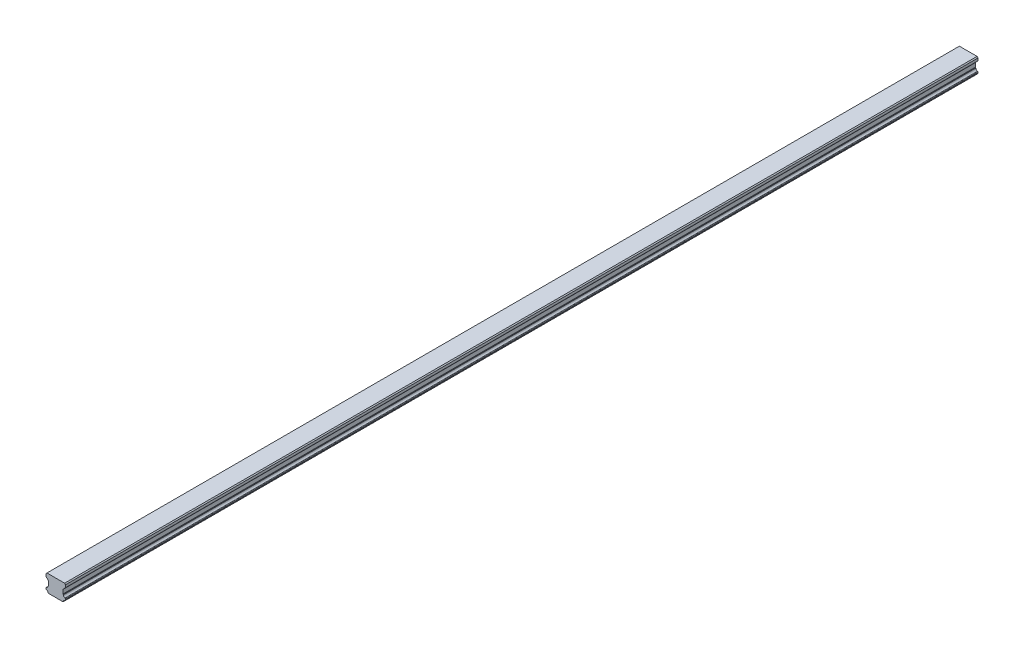
SolidWorks part; units mm, degrees
ref_plane "Спереди" through (0, 0, 0) normal (0, 0, 1) x (1, 0, 0)
ref_plane "Сверху" through (0, 0, 0) normal (0, 1, 0) x (1, 0, 0)
ref_plane "Справа" through (0, 0, 0) normal (1, 0, 0) x (0, 0, -1)
sketch "Эскиз1" plane through (0, 0, 0) normal (0, 0, 1) x (1, 0, 0)
  line L0 (-5.4699, -7.411) -> (5.7301, -7.411)
  line L1 (5.7301, -7.411) -> (5.8546, -7.2865)
  line L2 (7.3947, -5.7031) -> (7.6301, -5.1982)
  line L3 (7.6301, -5.1982) -> (7.6301, -4.7243)
  line L4 (7.6301, -4.7243) -> (7.3947, -4.2194)
  line L5 (5.8458, -2.5474) -> (5.718, -2.4196)
  line L6 (5.6301, -2.2075) -> (5.6301, 0.7647)
  line L7 (5.718, 0.9768) -> (7.5423, 2.8011)
  line L8 (7.6301, 3.0132) -> (7.6301, 4.8747)
  line L9 (7.6301, 4.8747) -> (6.9159, 5.589)
  line L10 (6.9159, 5.589) -> (-6.6556, 5.589)
  line L11 (-6.6556, 5.589) -> (-7.3699, 4.8747)
  line L12 (-7.3699, 4.8747) -> (-7.3699, 3.0132)
  line L13 (-7.282, 2.8011) -> (-5.4577, 0.9768)
  line L14 (-5.3699, 0.7647) -> (-5.3699, -2.2075)
  line L15 (-5.4577, -2.4196) -> (-5.5855, -2.5474)
  line L16 (-7.1344, -4.2194) -> (-7.3699, -4.7243)
  line L17 (-7.3699, -4.7243) -> (-7.3699, -5.1982)
  line L18 (-7.3699, -5.1982) -> (-7.1344, -5.7031)
  line L19 (-5.5943, -7.2865) -> (-5.4699, -7.411)
  arc A0 (5.8546, -7.2865) -> (5.9402, -7.1119) centre (5.6425, -7.0744) ccw
  arc A1 (7.1638, -5.8735) -> (5.9402, -7.1119) centre (7.3596, -7.2907) ccw
  arc A2 (7.1638, -5.8735) -> (7.3947, -5.7031) centre (7.1228, -5.5763) ccw
  arc A3 (7.3947, -4.2194) -> (7.1638, -4.049) centre (7.1228, -4.3462) ccw
  arc A4 (5.9328, -2.7374) -> (7.1638, -4.049) centre (7.3596, -2.6318) ccw
  arc A5 (5.9328, -2.7374) -> (5.8458, -2.5474) centre (5.6337, -2.7595) ccw
  arc A6 (5.6301, -2.2075) -> (5.718, -2.4196) centre (5.9301, -2.2075) ccw
  arc A7 (5.718, 0.9768) -> (5.6301, 0.7647) centre (5.9301, 0.7647) ccw
  arc A8 (7.5423, 2.8011) -> (7.6301, 3.0132) centre (7.3301, 3.0132) ccw
  arc A9 (-7.3699, 3.0132) -> (-7.282, 2.8011) centre (-7.0699, 3.0132) ccw
  arc A10 (-5.3699, 0.7647) -> (-5.4577, 0.9768) centre (-5.6699, 0.7647) ccw
  arc A11 (-5.4577, -2.4196) -> (-5.3699, -2.2075) centre (-5.6699, -2.2075) ccw
  arc A12 (-5.5855, -2.5474) -> (-5.6725, -2.7374) centre (-5.3734, -2.7595) ccw
  arc A13 (-6.9035, -4.049) -> (-5.6725, -2.7374) centre (-7.0993, -2.6318) ccw
  arc A14 (-6.9035, -4.049) -> (-7.1344, -4.2194) centre (-6.8625, -4.3462) ccw
  arc A15 (-7.1344, -5.7031) -> (-6.9035, -5.8735) centre (-6.8625, -5.5763) ccw
  arc A16 (-5.6799, -7.1119) -> (-6.9035, -5.8735) centre (-7.0993, -7.2907) ccw
  arc A17 (-5.6799, -7.1119) -> (-5.5943, -7.2865) centre (-5.3822, -7.0744) ccw
extrude "Бобышка-Вытянуть1" add sketch "Эскиз1" along normal blind 700
